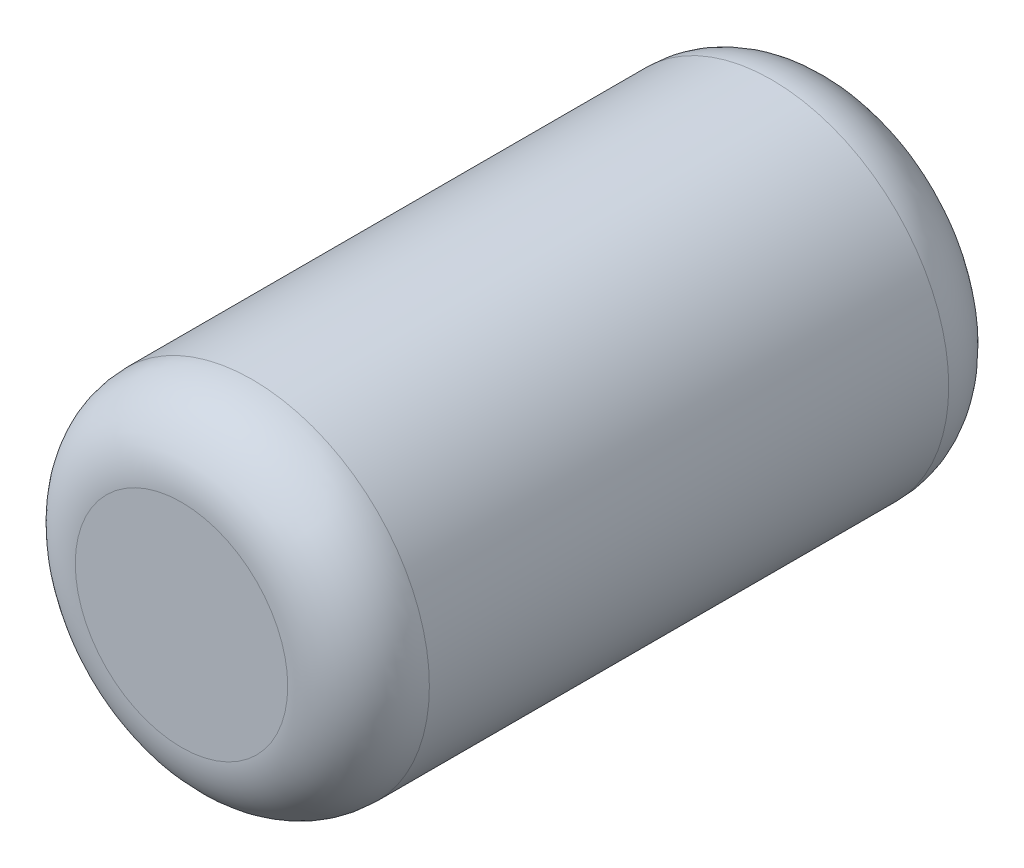
SolidWorks part; units mm, degrees
ref_plane "Front Plane" through (0, 0, 0) normal (0, 0, 1) x (1, 0, 0)
ref_plane "Top Plane" through (0, 0, 0) normal (0, 1, 0) x (1, 0, 0)
ref_plane "Right Plane" through (0, 0, 0) normal (1, 0, 0) x (0, 0, -1)
sketch "Sketch2" plane through (0, 0, 0) normal (0, 0, 1) x (1, 0, 0)
  circle A0 centre (0, 0) radius 7.5
  dimension "D1" = 15
extrude "Boss-Extrude1" add sketch "Sketch2" along normal blind 28
ref_point "Point1"
ref_point "Point2"
fillet "Fillet1" radius 3 2 edges at (7.5, 0, 28) (7.5, 0, 0)
